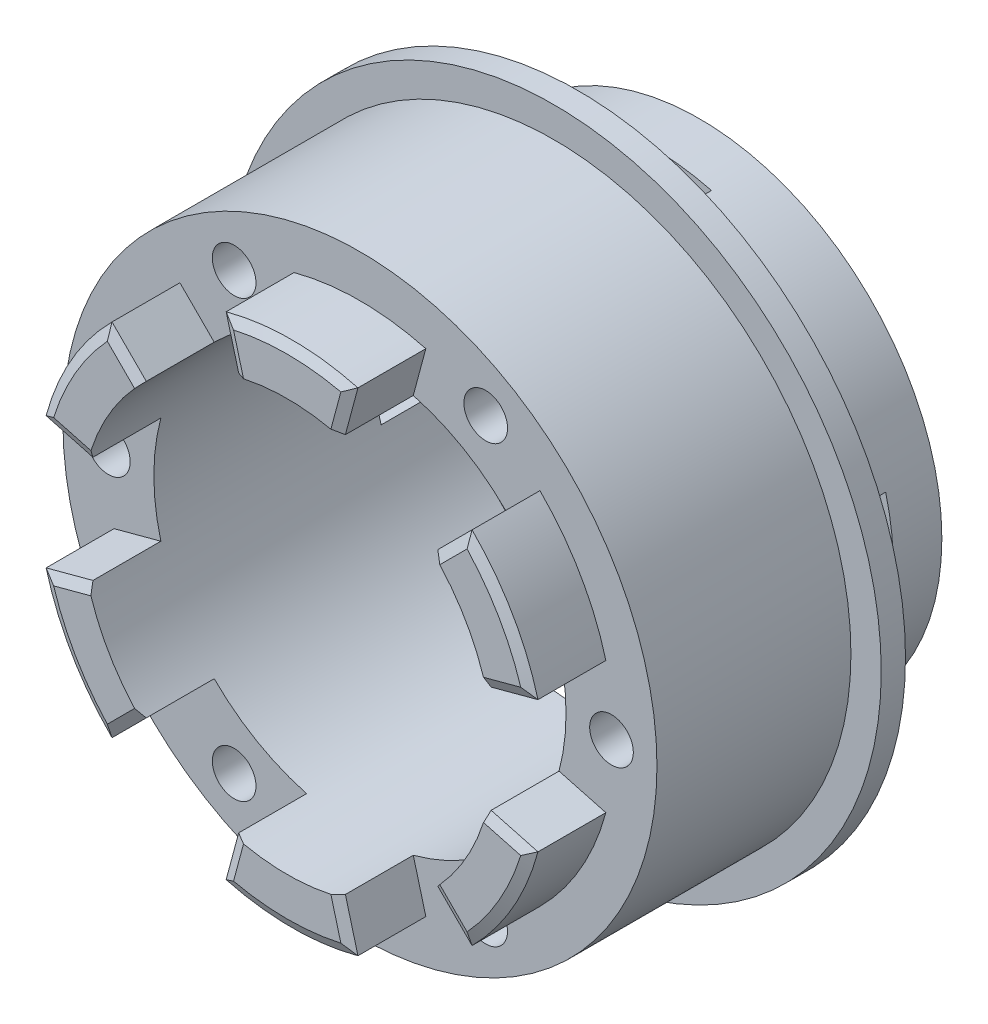
SolidWorks part; units mm, degrees
ref_plane "정면" through (0, 0, 0) normal (0, 0, 1) x (1, 0, 0)
ref_plane "윗면" through (0, 0, 0) normal (0, 1, 0) x (1, 0, 0)
ref_plane "우측면" through (0, 0, 0) normal (1, 0, 0) x (0, 0, -1)
sketch "스케치1" plane through (0, 0, 0) normal (0, 0, 1) x (1, 0, 0)
  circle A0 centre (0, 0) radius 10
  dimension "D1" = 20
extrude "보스-돌출1" add sketch "스케치1" along normal blind 2
sketch "스케치2" plane through (0, 0, 2) normal (0, 0, 1) x (1, 0, 0)
  circle A0 centre (0, 0) radius 10
  circle A1 centre (0, 0) radius 8.5
  circle A5 centre (0, 0) radius 10 construction
  dimension "D1" = 1.5
extrude "보스-돌출2" add sketch "스케치2" along normal blind 3
sketch "스케치4" plane through (0, 0, 5) normal (0, 0, 1) x (1, 0, 0)
  circle A0 centre (0, 0) radius 13.5
  circle A1 centre (0, 0) radius 8.5
  circle A2 centre (0, 0) radius 8.5 construction
  dimension "D1" = 27
extrude "보스-돌출3" add sketch "스케치4" along normal blind 1
sketch "스케치5" plane through (0, 0, 6) normal (0, 0, 1) x (1, 0, 0)
  circle A0 centre (0, 0) radius 8.5
  circle A1 centre (0, 0) radius 12.25
  circle A2 centre (0, 0) radius 8.5 construction
  dimension "D1" = 24.5
extrude "보스-돌출4" add sketch "스케치5" along normal blind 8
sketch "스케치6" plane through (0, 0, 14) normal (0, 0, 1) x (1, 0, 0)
  circle A0 centre (0, 0) radius 10.375 construction
  circle A6 centre (0, 0) radius 8.5 construction
  circle A8 centre (10.375, 0) radius 0.9
  circle A9 centre (5.1875, -8.985) radius 0.9
  circle A10 centre (-5.1875, -8.985) radius 0.9
  circle A11 centre (-10.375, 0) radius 0.9
  circle A12 centre (-5.1875, 8.985) radius 0.9
  circle A13 centre (5.1875, 8.985) radius 0.9
  point P19 (0, 0)
  point P20 (0, 0)
  dimension "D1" = 1.875
  dimension "D2" = 1.8
  dimension "D3" = 6
extrude "컷-돌출1" cut sketch "스케치6" against normal blind 8
sketch "스케치7" plane through (0, 0, 0) normal (0, 0, -1) x (-1, 0, 0)
  circle A0 centre (0, 0) radius 7 construction
  circle A5 centre (0, 0) radius 3
  circle A6 centre (-7, 0) radius 1.15
  circle A7 centre (7, 0) radius 1.15
  circle A9 centre (0, 7) radius 1.15
  circle A11 centre (0, -7) radius 1.15
  dimension "D1" = 14
  dimension "D2" = 2.3
  dimension "D4" = 6
extrude "컷-돌출2" cut sketch "스케치7" against normal through all
sketch "스케치8" plane through (0, 0, 0) normal (0, 1, 0) x (1, 0, 0)
  line L0 (10, 0) -> (-10, 0) construction
  line L1 (-2.5, -2) -> (2.5, -2)
  line L2 (-2.5, -2) -> (-2.5, -5)
  line L3 (-2.5, -5) -> (2.5, -5)
  line L4 (2.5, -2) -> (2.5, -5)
  line L5 (-2.5, -2) -> (2.5, -5) construction
  line L6 (-2.5, -5) -> (2.5, -2) construction
  line L8 (10, -5) -> (10, 0) construction
  line L9 (-10, 0) -> (-10, -5) construction
  line L10 (10, -5) -> (-10, -5) construction
  point P0 (0, -3.5)
  dimension "D1" = 2
  dimension "D3" = 7.5
  dimension "D4" = 7.5
extrude "컷-돌출3" cut sketch "스케치8" against normal through all both and the other way through all
sketch "스케치9" plane through (0, 0, 0) normal (1, 0, 0) x (0, 0, -1)
  line L0 (-5, -9.6825) -> (-5, 9.6825) construction
  line L1 (-5, -2.5) -> (-2, -2.5)
  line L2 (-5, -2.5) -> (-5, 2.5)
  line L3 (-5, 2.5) -> (-2, 2.5)
  line L4 (-2, -2.5) -> (-2, 2.5)
  line L5 (0, 10) -> (-2, 10) construction
  line L6 (-2, -10) -> (0, -10) construction
  line L7 (0, -10) -> (0, 10) construction
  dimension "D1" = 7.5
  dimension "D2" = 7.5
  dimension "D3" = 2
extrude "컷-돌출4" cut sketch "스케치9" against normal through all both and the other way through all
sketch "스케치10" plane through (0, 0, 14) normal (0, 0, 1) x (1, 0, 0)
  line L1 (2.2, 8.2104) -> (2.7176, 10.1422)
  line L3 (6.0104, 6.0104) -> (7.4246, 7.4246)
  line L5 (8.2104, 2.2) -> (10.1422, 2.7176)
  line L7 (8.2104, -2.2) -> (10.1422, -2.7176)
  line L9 (6.0104, -6.0104) -> (7.4246, -7.4246)
  line L11 (2.2, -8.2104) -> (2.7176, -10.1422)
  line L13 (-2.2, -8.2104) -> (-2.7176, -10.1422)
  line L15 (-6.0104, -6.0104) -> (-7.4246, -7.4246)
  line L17 (-8.2104, -2.2) -> (-10.1422, -2.7176)
  line L19 (-8.2104, 2.2) -> (-10.1422, 2.7176)
  line L21 (-6.0104, 6.0104) -> (-7.4246, 7.4246)
  line L23 (-2.2, 8.2104) -> (-2.7176, 10.1422)
  arc A0 (-7.4246, 7.4246) -> (-10.1422, 2.7176) centre (0, 0) ccw
  arc A1 (-8.2104, -2.2) -> (-6.0104, -6.0104) centre (0, 0) ccw
  arc A2 (2.7176, 10.1422) -> (-2.7176, 10.1422) centre (0, 0) ccw
  arc A3 (10.1422, 2.7176) -> (7.4246, 7.4246) centre (0, 0) ccw
  arc A4 (7.4246, -7.4246) -> (10.1422, -2.7176) centre (0, 0) ccw
  arc A5 (-2.7176, -10.1422) -> (2.7176, -10.1422) centre (0, 0) ccw
  arc A6 (-10.1422, -2.7176) -> (-7.4246, -7.4246) centre (0, 0) ccw
  arc A7 (-2.2, -8.2104) -> (2.2, -8.2104) centre (0, 0) ccw
  arc A8 (6.0104, -6.0104) -> (8.2104, -2.2) centre (0, 0) ccw
  arc A9 (8.2104, 2.2) -> (6.0104, 6.0104) centre (0, 0) ccw
  arc A10 (2.2, 8.2104) -> (-2.2, 8.2104) centre (0, 0) ccw
  arc A11 (-6.0104, 6.0104) -> (-8.2104, 2.2) centre (0, 0) ccw
  circle A12 centre (0, 0) radius 8.5 construction
  arc A13 (8.124, 2.5) -> (2.5, 8.124) centre (0, 0) ccw construction
  point P30 (0, 0)
  dimension "D1" = 2
extrude "보스-돌출5" add sketch "스케치10" along normal blind 3
chamfer "모따기1" distance 0.2 angle 64 18 edges at (-9.1763, -2.4588, 17) (-6.7175, -6.7175, 17) (-2.4588, -9.1763, 17) (2.4588, -9.1763, 17) (6.7175, -6.7175, 17) (9.1763, -2.4588, 17) (9.1763, 2.4588, 17) (6.7175, 6.7175, 17) (2.4588, 9.1763, 17) (-2.4588, 9.1763, 17) (-6.7175, 6.7175, 17) (-9.1763, 2.4588, 17) (-9.0933, -5.25, 17) (0, -10.5, 17) (9.0933, -5.25, 17) (9.0933, 5.25, 17) (0, 10.5, 17) (-9.0933, 5.25, 17)
